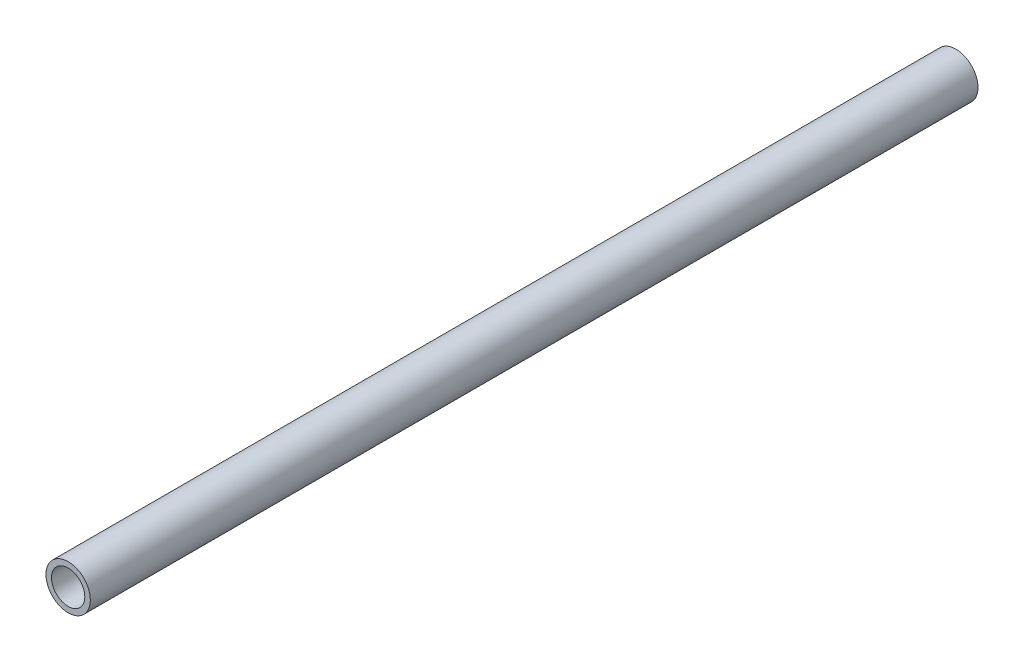
SolidWorks part; units mm, degrees
ref_plane "Front Plane" through (0, 0, 0) normal (0, 0, 1) x (1, 0, 0)
ref_plane "Top Plane" through (0, 0, 0) normal (0, 1, 0) x (1, 0, 0)
ref_plane "Right Plane" through (0, 0, 0) normal (1, 0, 0) x (0, 0, -1)
sketch "Sketch1" plane through (0, 0, 0) normal (0, 0, 1) x (1, 0, 0)
  circle A0 centre (0, 0) radius 1
  dimension "D1" = 2
extrude "Boss-Extrude1" add sketch "Sketch1" along normal blind 40
sketch "Sketch2" plane through (0, 0, 40) normal (0, 0, 1) x (1, 0, 0)
  circle A0 centre (0, 0) radius 0.75
  dimension "D1" = 1.5
extrude "Cut-Extrude1" cut sketch "Sketch2" against normal blind 40
